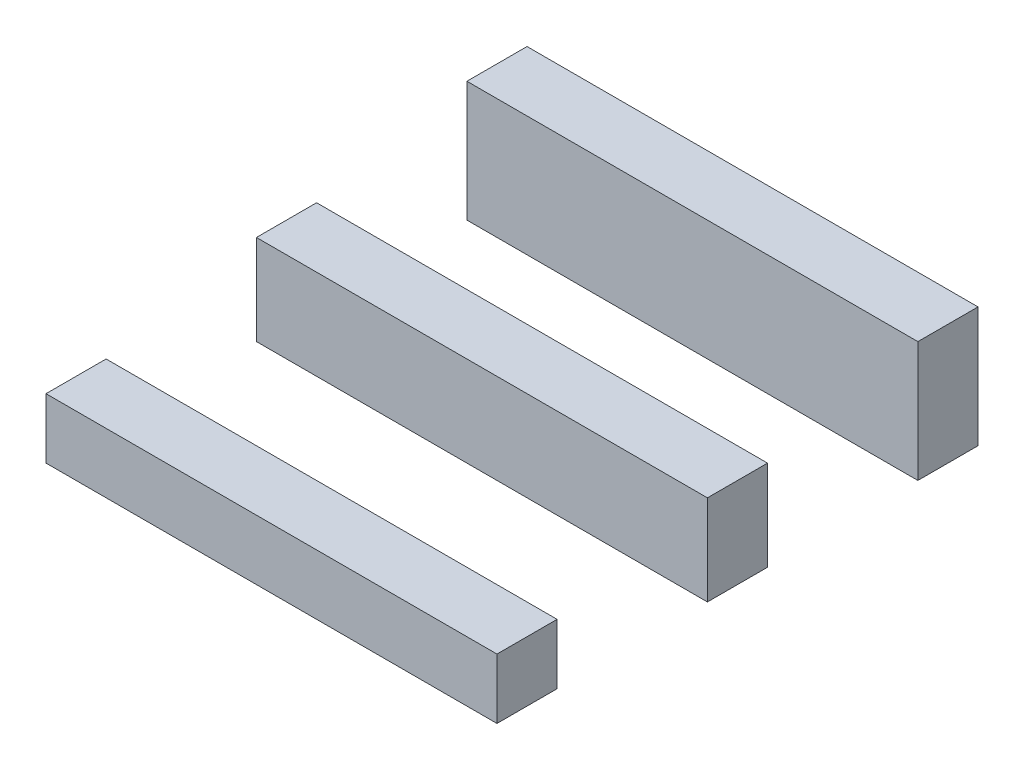
SolidWorks part; units mm, degrees
ref_plane "Front Plane" through (0, 0, 0) normal (0, 0, 1) x (1, 0, 0)
ref_plane "Top Plane" through (0, 0, 0) normal (0, 1, 0) x (1, 0, 0)
ref_plane "Right Plane" through (0, 0, 0) normal (1, 0, 0) x (0, 0, -1)
ref_plane "Plane1" through (0, 1, 0) normal (0, 1, 0) x (1, 0, 0)
sketch "Sketch1" plane through (0, 0, 0) normal (0, 1, 0) x (1, 0, 0)
  line L1 (25, -25) -> (-25, -25)
  line L2 (25, -25) -> (25, 25)
  line L3 (25, 25) -> (-25, 25)
  line L4 (-25, -25) -> (-25, 25)
  line L5 (25, -25) -> (-25, 25) construction
  line L6 (25, 25) -> (-25, -25) construction
  point P0 (0, 0)
  dimension "D1" = 50
  dimension "D2" = 50
sketch "Sketch2" plane through (0, 1, 0) normal (0, 1, 0) x (1, 0, 0)
  line L0 (25, -25) -> (-25, -25) construction
  line L1 (25, -25) -> (25, 25) construction
  line L10 (-15, -12) -> (15, -12)
  line L11 (-15, -12) -> (-15, -16)
  line L12 (-15, -16) -> (15, -16)
  line L13 (15, -12) -> (15, -16)
  point P2 (0, -25)
  dimension "D1" = 9
  dimension "D2" = 10
  dimension "D3" = 30
  dimension "D6" = 4
extrude "Boss-Extrude1" add sketch "Sketch2" along normal blind 4
sketch "Sketch3" plane through (0, 1, 0) normal (0, 1, 0) x (1, 0, 0)
  line L1 (-15, 2) -> (15, 2)
  line L2 (-15, 2) -> (-15, -2)
  line L3 (-15, -2) -> (15, -2)
  line L4 (15, 2) -> (15, -2)
  line L5 (15, -16) -> (15, -12) construction
  line L6 (15, -12) -> (-15, -12) construction
  dimension "D1" = 30
  dimension "D2" = 0
  dimension "D3" = 4
  dimension "D4" = 10
extrude "Boss-Extrude2" add sketch "Sketch3" along normal blind 6 separate body
sketch "Sketch4" plane through (0, 1, 0) normal (0, 1, 0) x (1, 0, 0)
  line L0 (15, 2) -> (-15, 2) construction
  line L1 (-15, 16) -> (15, 16)
  line L2 (-15, 16) -> (-15, 12)
  line L3 (-15, 12) -> (15, 12)
  line L4 (15, 16) -> (15, 12)
  line L5 (25, -25) -> (25, 25) construction
  dimension "D1" = 10
  dimension "D2" = 4
  dimension "D3" = 30
  dimension "D4" = 10
extrude "Boss-Extrude3" add sketch "Sketch4" along normal blind 8 separate body
